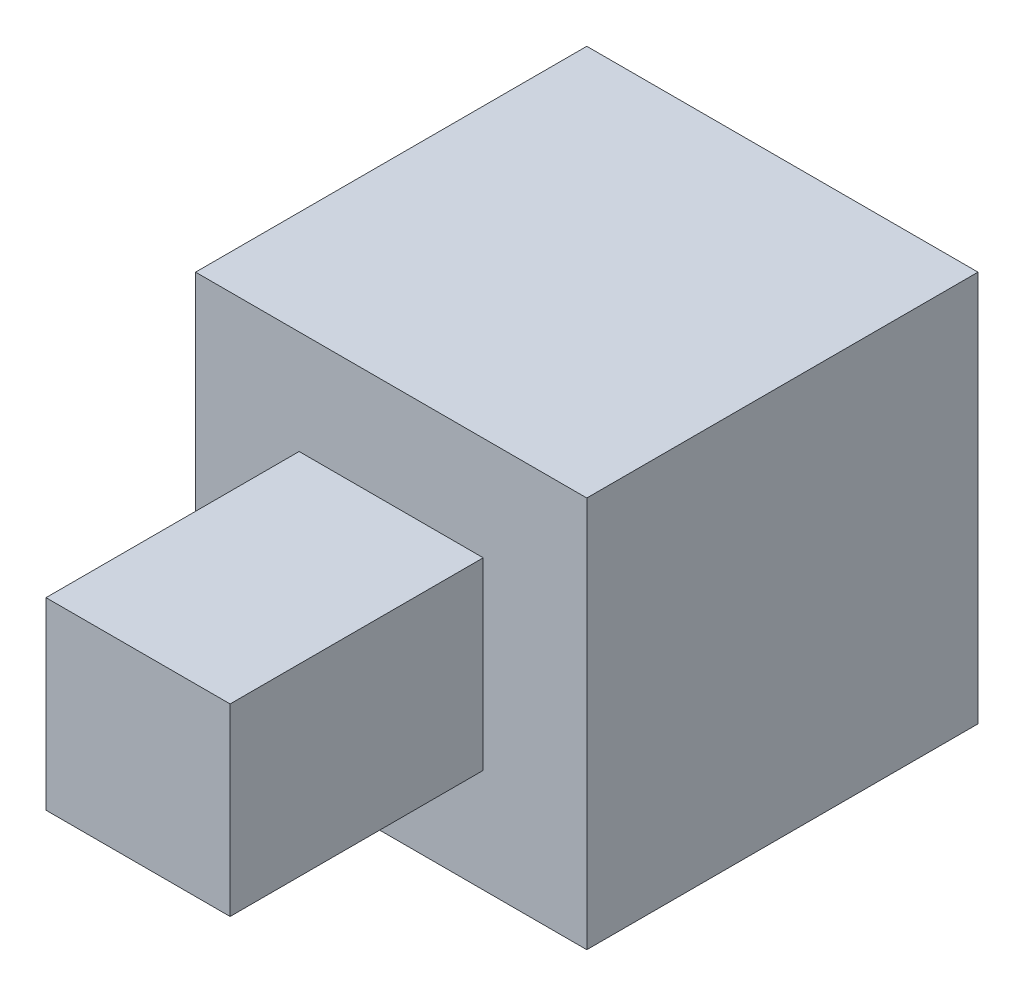
SolidWorks part; units mm, degrees
ref_plane "Front Plane" through (0, 0, 0) normal (0, 0, 1) x (1, 0, 0)
ref_plane "Top Plane" through (0, 0, 0) normal (0, 1, 0) x (1, 0, 0)
ref_plane "Right Plane" through (0, 0, 0) normal (1, 0, 0) x (0, 0, -1)
sketch "Sketch1" plane through (0, 0, 0) normal (0, 0, 1) x (1, 0, 0)
  line L1 (-4.25, 4.25) -> (4.25, 4.25)
  line L2 (-4.25, 4.25) -> (-4.25, -4.25)
  line L3 (-4.25, -4.25) -> (4.25, -4.25)
  line L4 (4.25, 4.25) -> (4.25, -4.25)
  line L5 (-4.25, 4.25) -> (4.25, -4.25) construction
  line L6 (-4.25, -4.25) -> (4.25, 4.25) construction
  point P0 (0, 0)
  dimension "D1" = 8.5
extrude "Boss-Extrude1" add sketch "Sketch1" along normal blind 8.5
sketch "Sketch2" plane through (0, 0, 8.5) normal (0, 0, 1) x (1, 0, 0)
  line L1 (-2, 2) -> (2, 2)
  line L2 (-2, 2) -> (-2, -2)
  line L3 (-2, -2) -> (2, -2)
  line L4 (2, 2) -> (2, -2)
  line L5 (-2, 2) -> (2, -2) construction
  line L6 (-2, -2) -> (2, 2) construction
  point P0 (0, 0)
  dimension "D1" = 4
extrude "Boss-Extrude2" add sketch "Sketch2" along normal blind 5.5
